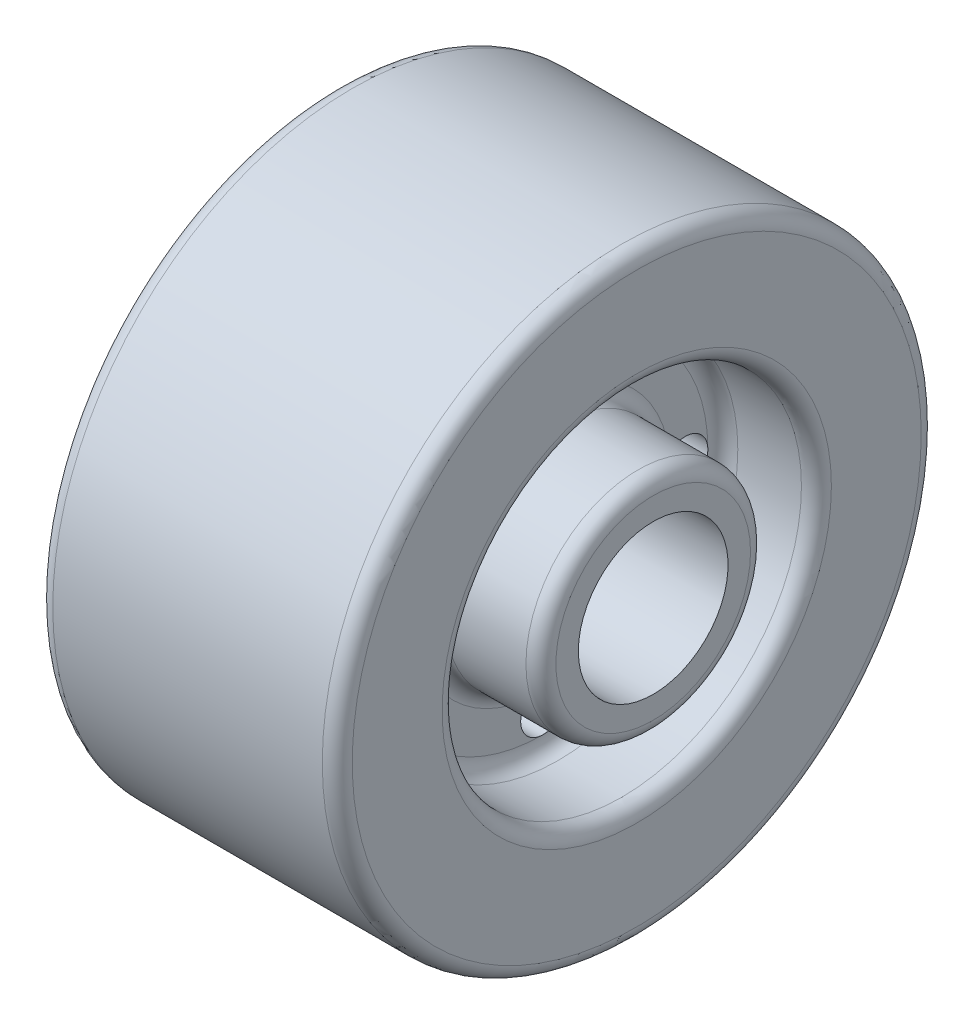
SolidWorks part; units mm, degrees
ref_plane "Front Plane" through (0, 0, 0) normal (0, 0, 1) x (1, 0, 0)
ref_plane "Top Plane" through (0, 0, 0) normal (0, 1, 0) x (1, 0, 0)
ref_plane "Right Plane" through (0, 0, 0) normal (1, 0, 0) x (0, 0, -1)
sketch "Sketch1" plane through (0, 0, 0) normal (0, 0, 1) x (1, 0, 0)
  line L0 (-20, -40) -> (20, -40)
  line L1 (20, -40) -> (20, -24)
  line L2 (20, -24) -> (7.5, -24)
  line L3 (7.5, -24) -> (7.5, -15)
  line L4 (7.5, -15) -> (22.2, -15)
  line L5 (22.2, -15) -> (22.2, -6)
  line L6 (0, -40) -> (0, 0) construction
  line L7 (0, 0) -> (22.2, 0) construction
  line L8 (22.2, -6) -> (-22.2, -6)
  line L9 (-22.2, -15) -> (-22.2, -6)
  line L10 (-7.5, -15) -> (-22.2, -15)
  line L11 (-7.5, -24) -> (-7.5, -15)
  line L12 (-20, -24) -> (-7.5, -24)
  line L13 (-20, -40) -> (-20, -24)
  point P12 (0, -6)
  dimension "D1" = 44.4
  dimension "D2" = 40
  dimension "D3" = 12
  dimension "D4" = 30
  dimension "D5" = 80
  dimension "D6" = 16
  dimension "D7" = 15
revolve "Revolve1" add sketch "Sketch1" angle 360 about L7
fillet "Fillet1" radius 2 10 edges at (7.5, 0, 24) (7.5, 0, 15) (-7.5, 0, 15) (-7.5, 0, 24) (-20, 0, 24) (20, 0, 24) (-20, 0, 40) (20, 0, 40) (22.2, 0, 15) (-22.2, 0, 15)
sketch "Sketch2" plane through (-22.2, 0, 0) normal (-1, 0, 0) x (0, 0, 1)
  circle A0 centre (0, 0) radius 10
  dimension "D1" = 20
extrude "centrebored out" cut sketch "Sketch2" against normal through all
sketch "Sketch3" plane through (-7.5, 0, 0) normal (-1, 0, 0) x (0, 0, 1)
  line L0 (0, 19) -> (0, 0) construction
  circle A0 centre (0, 19) radius 3
  circle A1 centre (19, 0) radius 3
  circle A2 centre (0, -19) radius 3
  circle A3 centre (-19, 0) radius 3
  point P13 (0, 0)
  dimension "D1" = 6
  dimension "D2" = 19
extrude "Cut-Extrude2" cut sketch "Sketch3" against normal blind 20 and the other way blind 10
sketch "Sketch4" plane through (-7.5, 0, 0) normal (-1, 0, 0) x (0, 0, 1)
  circle A0 centre (0, 19) radius 6
  circle A1 centre (-19, 0) radius 6
  circle A2 centre (19, 0) radius 6
  circle A3 centre (0, -19) radius 6
  dimension "D1" = 12
extrude "Cut-Extrude3" cut sketch "Sketch4" along normal through all
